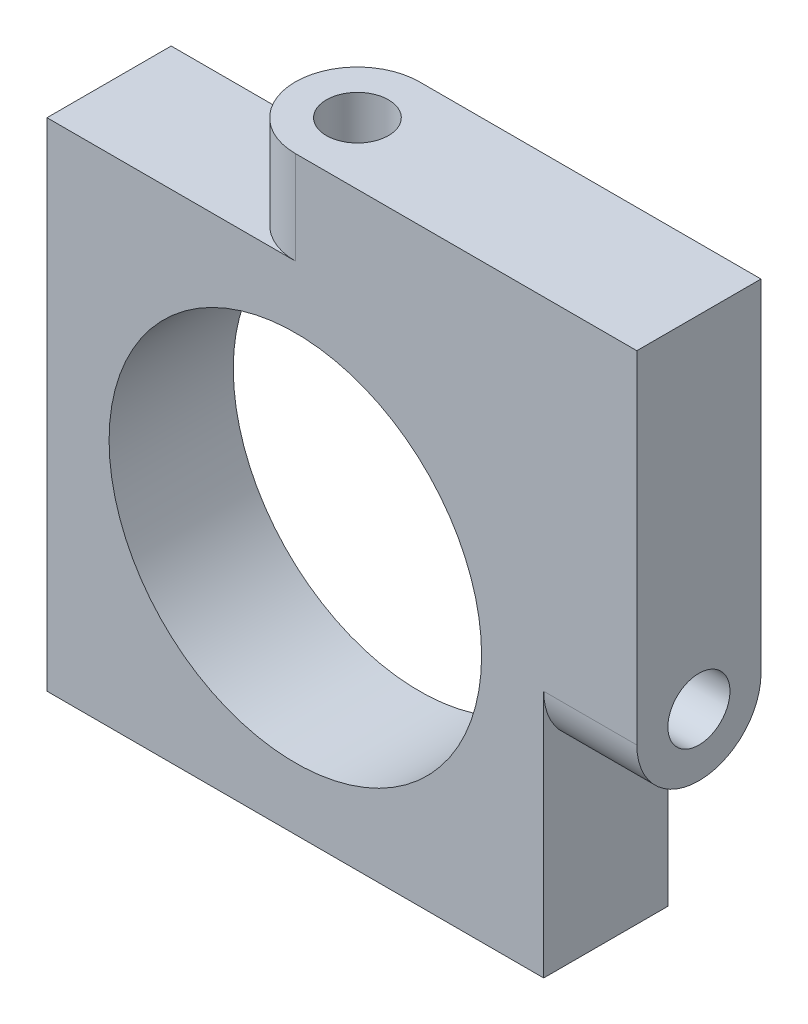
SolidWorks part; units mm, degrees
ref_plane "Front Plane" through (0, 0, 0) normal (0, 0, 1) x (1, 0, 0)
ref_plane "Top Plane" through (0, 0, 0) normal (0, 1, 0) x (1, 0, 0)
ref_plane "Right Plane" through (0, 0, 0) normal (1, 0, 0) x (0, 0, -1)
sketch "Sketch2" plane through (0, 0, 0) normal (0, 0, 1) x (1, 0, 0)
  line L1 (0, 0) -> (101.6, 0)
  line L2 (0, 0) -> (0, 101.6)
  line L3 (0, 101.6) -> (101.6, 101.6)
  line L4 (101.6, 0) -> (101.6, 101.6)
  circle A0 centre (50.8, 50.8) radius 38.1
  dimension "D3" = 76.2
  dimension "D1" = 101.6
  dimension "D2" = 101.6
  dimension "D4" = 50.8
  dimension "D5" = 50.8
extrude "Boss-Extrude1" add sketch "Sketch2" along normal blind 25.4
sketch "Sketch3" plane through (0, 101.6, 0) normal (0, 1, 0) x (1, 0, 0)
  line L0 (101.6, -25.4) -> (0, -25.4) construction
  line L1 (101.6, 0) -> (50.8, 0)
  line L2 (101.6, 0) -> (101.6, -25.4)
  line L3 (101.6, -25.4) -> (50.8, -25.4)
  line L4 (50.8, 0) -> (50.8, -25.4)
  arc A0 (50.8, 0) -> (50.8, -25.4) centre (50.8, -12.7) ccw
  circle A1 centre (50.8, -12.7) radius 6.35
  line M1 (101.6, 0) -> (0, 0)
  line M3 (0, -25.4) -> (101.6, -25.4)
  line M4 (101.6, -25.4) -> (101.6, 0)
  dimension "D1" = 12.7
  dimension "D2" = 12.7
  dimension "D3" = 25.4
extrude "Boss-Extrude2" add sketch "Sketch3" along normal blind 19.05 contours A1 L4 A0 | A1 L4 M3 M4 M1
sketch "Sketch4" plane through (101.6, 0, 0) normal (1, 0, 0) x (0, 0, -1)
  line L0 (0, 0) -> (0, 120.65) construction
  line L1 (-25.4, 120.65) -> (0, 120.65)
  line L2 (-25.4, 120.65) -> (-25.4, 50.8)
  line L3 (-25.4, 50.8) -> (0, 50.8)
  line L4 (0, 120.65) -> (0, 50.8)
  arc A0 (-25.4, 50.8) -> (0, 50.8) centre (-12.7, 50.8) ccw
  circle A1 centre (-12.7, 50.8) radius 6.35
  line M2 (0, 0) -> (0, 120.65)
  line M3 (0, 120.65) -> (-25.4, 120.65)
  line M4 (-25.4, 120.65) -> (-25.4, 0)
  dimension "D2" = 12.7
  dimension "D1" = 69.85
extrude "Boss-Extrude3" add sketch "Sketch4" along normal blind 19.05 contours A1 L3 A0 | A1 L3 M2 M3 M4
